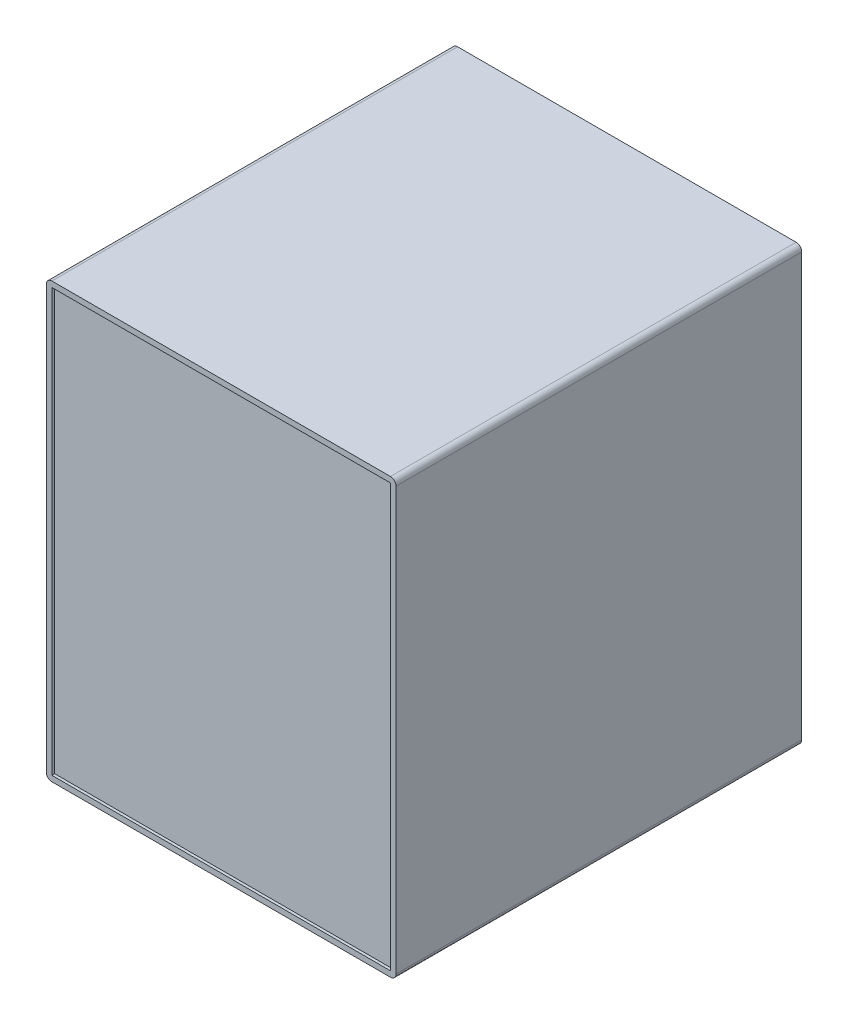
SolidWorks part; units mm, degrees
ref_plane "Front Plane" through (0, 0, 0) normal (0, 0, 1) x (1, 0, 0)
ref_plane "Top Plane" through (0, 0, 0) normal (0, 1, 0) x (1, 0, 0)
ref_plane "Right Plane" through (0, 0, 0) normal (1, 0, 0) x (0, 0, -1)
sketch "Sketch1" plane through (0, 0, 0) normal (0, 0, 1) x (1, 0, 0)
  line L1 (0, 0) -> (125, 0)
  line L2 (0, 0) -> (0, 155)
  line L3 (0, 155) -> (125, 155)
  line L4 (125, 0) -> (125, 155)
  dimension "D1" = 155
  dimension "D2" = 125
extrude "Boss-Extrude1" add sketch "Sketch1" along normal blind 145
sketch "Sketch2" plane through (0, 0, 145) normal (0, 0, 1) x (1, 0, 0)
  line L0 (0, 155) -> (0, 0) construction
  line L1 (2, 153) -> (123, 153)
  line L2 (2, 153) -> (2, 2)
  line L3 (2, 2) -> (123, 2)
  line L4 (123, 153) -> (123, 2)
  line L5 (125, 155) -> (0, 155) construction
  line L6 (125, 0) -> (125, 155) construction
  line L7 (0, 0) -> (125, 0) construction
  dimension "D1" = 2
  dimension "D2" = 2
  dimension "D3" = 2
  dimension "D4" = 2
extrude "Cut-Extrude1" cut sketch "Sketch2" against normal blind 1
fillet "Fillet1" radius 2 3 edges at (0, 0, 72.5) (125, 155, 72.5) (0, 155, 72.5)
fillet "Fillet2" radius 2 1 edges at (125, 0, 72.5)
hole_wizard "Ø10.0mm Dowel Hole1" positions "3DSketch1" profile "Sketch4" hole size "Ø10.0" standard "ISO"
sketch3d "3DSketch1"
  line L0 (125, 2, 145) -> (125, 2, 0) construction
  line L1 (2, 0, 145) -> (123, 0, 145) construction
  point P0 (62.532, 0, 72.5)
  dimension "D1" = 62.5
  dimension "D2" = 72.5
sketch "Sketch4" plane through (62.532, 0, 72.5) normal (1, 0, 0) x (0, 0, -1)
  line L0 (0, 0) -> (0, 23.0043)
  line L1 (0, 23.0043) -> (5, 20)
  line L2 (5, 20) -> (5, 0)
  line L5 (5, 0) -> (0, 0)
  line L10 (0, 23.0043) -> (-5, 20) construction
  line L11 (0, -6.35) -> (0, 107.95) construction
  dimension "Hole Dia." = 10
  dimension "Hole Depth" = 20
  dimension "Drill Angle" = 118
